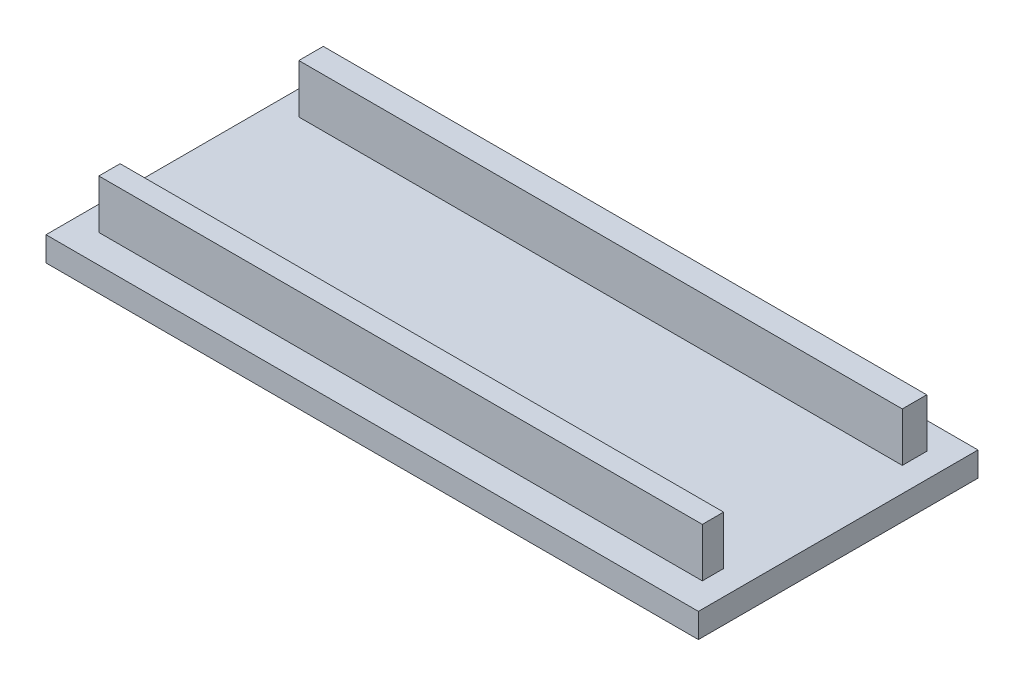
SolidWorks part; units mm, degrees
ref_plane "前视基准面" through (0, 0, 0) normal (0, 0, 1) x (1, 0, 0)
ref_plane "上视基准面" through (0, 0, 0) normal (0, 1, 0) x (1, 0, 0)
ref_plane "右视基准面" through (0, 0, 0) normal (1, 0, 0) x (0, 0, -1)
sketch "草图2" plane through (0, 0, 0) normal (0, 1, 0) x (1, 0, 0)
  line L1 (-49.6615, 4.4425) -> (3.6785, 4.4425)
  line L2 (-49.6615, 4.4425) -> (-49.6615, -18.4175)
  line L3 (-49.6615, -18.4175) -> (3.6785, -18.4175)
  line L4 (3.6785, 4.4425) -> (3.6785, -18.4175)
extrude "凸台-拉伸1" add sketch "草图2" along normal blind 2
sketch "草图3" plane through (0, 2, 0) normal (0, 1, 0) x (1, 0, 0)
  line L1 (-49.6615, 4.4425) -> (-49.6615, -18.4175) construction
  line L2 (-47.6615, 2.2527) -> (1.6785, 2.2527)
  line L3 (1.6785, 2.2527) -> (1.6785, 0.2527)
  line L4 (1.6785, 0.2527) -> (-47.6615, 0.2527)
  line L5 (-47.6615, 0.2527) -> (-47.6615, 2.2527)
  line L6 (-47.6615, -14.358) -> (-47.6615, -16.0974)
  line L7 (-47.6615, -16.0974) -> (1.6785, -16.0974)
  line L8 (1.6785, -16.0974) -> (1.6785, -14.358)
  line L9 (1.6785, -14.358) -> (-47.6615, -14.358)
  line L10 (3.6785, -18.4175) -> (3.6785, 4.4425) construction
  point P4 (-49.6615, -6.9875)
  point P8 (-47.6615, -15.2277)
  point P11 (-47.6615, 1.2527)
  dimension "D2" = 2
extrude "凸台-拉伸2" add sketch "草图3" along normal blind 4
